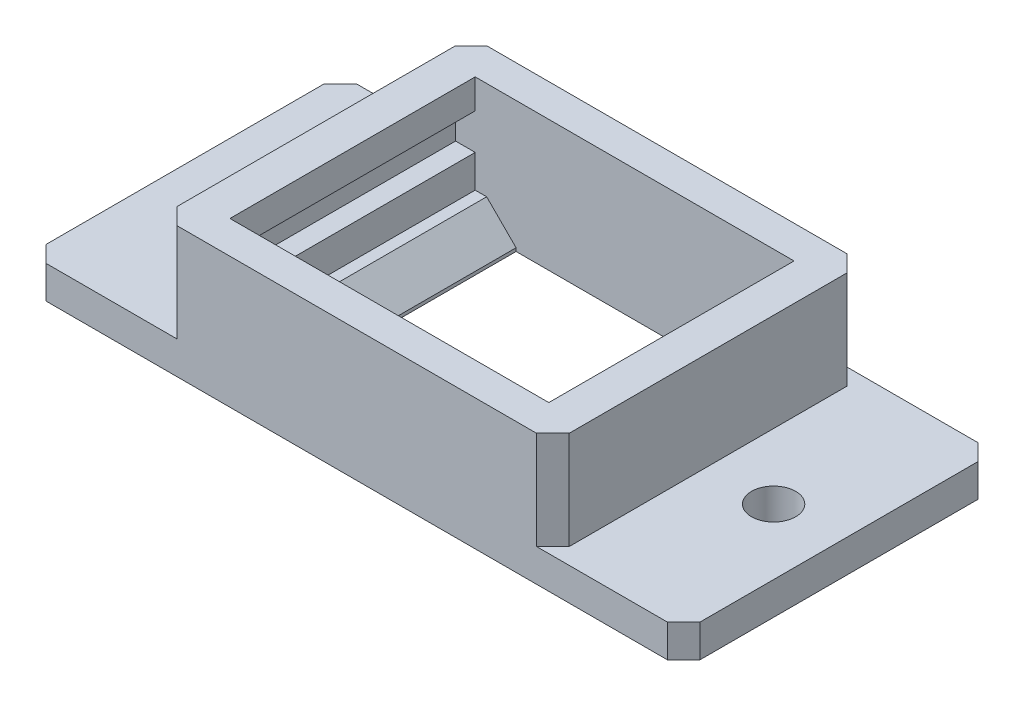
SolidWorks part; units mm, degrees
ref_plane "Спереди" through (0, 0, 0) normal (0, 0, 1) x (1, 0, 0)
ref_plane "Сверху" through (0, 0, 0) normal (0, 1, 0) x (1, 0, 0)
ref_plane "Справа" through (0, 0, 0) normal (1, 0, 0) x (0, 0, -1)
sketch "Эскиз1" plane through (0, 0, 0) normal (0, 1, 0) x (1, 0, 0)
  line L1 (20, -9.5) -> (-20, -9.5)
  line L2 (20, -9.5) -> (20, 9.5)
  line L3 (20, 9.5) -> (-20, 9.5)
  line L4 (-20, -9.5) -> (-20, 9.5)
  line L5 (20, -9.5) -> (-20, 9.5) construction
  line L6 (20, 9.5) -> (-20, -9.5) construction
  point P0 (0, 0)
  dimension "D1" = 40
  dimension "D2" = 19
extrude "Бобышка-Вытянуть1" add sketch "Эскиз1" along normal blind 8
sketch "Эскиз2" plane through (0, 8, 0) normal (0, 1, 0) x (1, 0, 0)
  line L0 (20, 9.5) -> (-20, 9.5) construction
  line L1 (12, -9.5) -> (-12, -9.5)
  line L2 (12, -9.5) -> (12, 9.5)
  line L3 (12, 9.5) -> (-12, 9.5)
  line L4 (-12, -9.5) -> (-12, 9.5)
  line L5 (12, -9.5) -> (-12, 9.5) construction
  line L6 (12, 9.5) -> (-12, -9.5) construction
  line L7 (21, -10.5) -> (-21, -10.5)
  line L8 (21, -10.5) -> (21, 10.5)
  line L9 (21, 10.5) -> (-21, 10.5)
  line L10 (-21, -10.5) -> (-21, 10.5)
  line L11 (21, -10.5) -> (-21, 10.5) construction
  line L12 (21, 10.5) -> (-21, -10.5) construction
  line L13 (-20, 9.5) -> (-20, -9.5) construction
  point P0 (0, 0)
  point P5 (0, 0)
  dimension "D1" = 1
  dimension "D2" = 1
  dimension "D3" = 24
  dimension "D4" = 19
extrude "Вырез-Вытянуть1" cut sketch "Эскиз2" against normal blind 6
sketch "Эскиз3" plane through (0, 8, 0) normal (0, 1, 0) x (1, 0, 0)
  line L1 (9.75, -7.5) -> (-9.75, -7.5)
  line L2 (9.75, -7.5) -> (9.75, 7.5)
  line L3 (9.75, 7.5) -> (-9.75, 7.5)
  line L4 (-9.75, -7.5) -> (-9.75, 7.5)
  line L5 (9.75, -7.5) -> (-9.75, 7.5) construction
  line L6 (9.75, 7.5) -> (-9.75, -7.5) construction
  point P0 (0, 0)
  dimension "D1" = 19.5
  dimension "D2" = 15
extrude "Вырез-Вытянуть2" cut sketch "Эскиз3" against normal blind 6
sketch "Эскиз5" plane through (0, 2, 0) normal (0, 1, 0) x (1, 0, 0)
  line L0 (-9.75, -7.5) -> (9.75, -7.5) construction
  line L1 (9.75, 7.5) -> (-7.25, 7.5)
  line L2 (9.75, 7.5) -> (9.75, -7.5)
  line L3 (9.75, -7.5) -> (-7.25, -7.5)
  line L4 (-7.25, 7.5) -> (-7.25, -7.5)
  dimension "D1" = 17
extrude "Вырез-Вытянуть3" cut sketch "Эскиз5" against normal blind 8
sketch "Эскиз6" plane through (-9.75, 0, 0) normal (1, 0, 0) x (0, 0, -1)
  line L0 (-7.5, 2) -> (-7.5, 8) construction
  line L1 (-7.5, 6.2) -> (7.5, 6.2)
  line L2 (-7.5, 6.2) -> (-7.5, 4)
  line L3 (-7.5, 4) -> (7.5, 4)
  line L4 (7.5, 6.2) -> (7.5, 4)
  line L5 (7.5, 8) -> (-7.5, 8) construction
  line L6 (7.5, 2) -> (7.5, 8) construction
  line L7 (7.5, 2) -> (-7.5, 2) construction
  dimension "D1" = 0
  dimension "D2" = 1.8
  dimension "D3" = 0
  dimension "D4" = 2
extrude "Вырез-Вытянуть4" cut sketch "Эскиз6" against normal blind 1.2
mirror "Зеркальное отражение1" about plane through (0, 0, 0) normal (1, 0, 0) of "Вырез-Вытянуть4"
chamfer "Фаска1" distance 1.8 angle 45 1 edges
chamfer "Фаска2" distance 1 angle 45 4 edges at (-12, 5, -9.5) (12, 5, -9.5) (12, 5, 9.5) (-12, 5, 9.5)
chamfer "Фаска3" distance 1 angle 45 4 edges at (20, 1, 9.5) (20, 1, -9.5) (-20, 1, 9.5) (-20, 1, -9.5)
sketch "Эскиз7" plane through (0, 2, 0) normal (0, 1, 0) x (1, 0, 0)
  circle A0 centre (-16, 0) radius 1.35
  circle A1 centre (16, 0) radius 1.35
  dimension "D1" = 0
  dimension "D5" = 2.7
  dimension "D6" = 2.7
  dimension "D2" = 0
  dimension "D3" = 16
  dimension "D4" = 16
extrude "Вырез-Вытянуть5" cut sketch "Эскиз7" against normal through all
